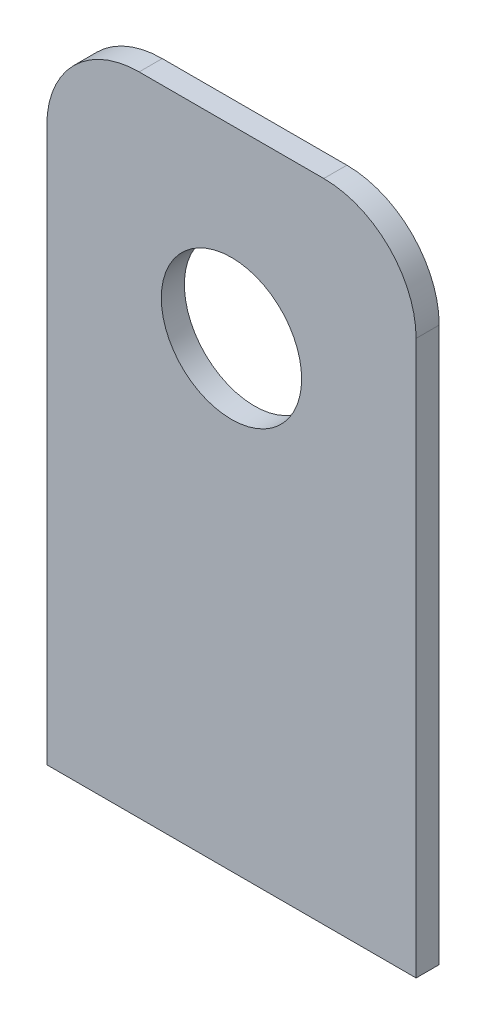
SolidWorks part; units mm, degrees
material "AISI 4130 Steel, annealed at 865C"
ref_plane "Front Plane" through (0, 0, 0) normal (0, 0, 1) x (1, 0, 0)
ref_plane "Top Plane" through (0, 0, 0) normal (0, 1, 0) x (1, 0, 0)
ref_plane "Right Plane" through (0, 0, 0) normal (1, 0, 0) x (0, 0, -1)
sketch "Sketch1" plane through (0, 0, 0) normal (0, 0, 1) x (1, 0, 0)
  line L1 (-12.7, 0) -> (12.7, 0)
  line L2 (-12.7, 0) -> (-12.7, 31.75)
  line L3 (-12.7, 31.75) -> (12.7, 31.75)
  line L4 (12.7, 0) -> (12.7, 31.75)
  line L5 (0, 31.75) -> (0, 0) construction
  line L6 (-12.7, 15.875) -> (12.7, 15.875) construction
  point P248 (0, 15.875)
  dimension "D1" = 25.4
  dimension "D2" = 31.75
extrude "Boss-Extrude1" add sketch "Sketch1" along normal blind 1.5875
sketch "Sketch2" plane through (0, 0, 1.5875) normal (0, 0, 1) x (1, 0, 0)
  line L0 (0, 0) -> (0, 19.05) construction
  line L1 (-12.7, 0) -> (12.7, 0) construction
  circle A0 centre (0, 19.05) radius 4.826
  dimension "D2" = 9.652
  dimension "D1" = 19.05
extrude "Cut-Extrude1" cut sketch "Sketch2" against normal through all both and the other way through all
fillet "Fillet1" radius 6.35 2 edges at (12.7, 31.75, 0.7937) (-12.7, 31.75, 0.7937)
sketch "Sketch3" plane through (0, 0, 0) normal (0, 0, -1) x (-1, 0, 0)
  line L0 (12.7, 25.4) -> (12.7, 0) construction
  line L1 (-12.7, 0) -> (12.7, 0)
  line L2 (-12.7, 0) -> (-12.7, -12.7)
  line L3 (-12.7, -12.7) -> (12.7, -12.7)
  line L4 (12.7, 0) -> (12.7, -12.7)
  line L5 (0, -12.7) -> (0, 0) construction
  line L6 (-12.7, -6.35) -> (12.7, -6.35) construction
  point P112 (0, -6.35)
  dimension "D1" = 12.7
extrude "Boss-Extrude2" add sketch "Sketch3" against normal up to surface (1.5875 mm away) up to face at (-4.826, 19.05, 1.5875)
